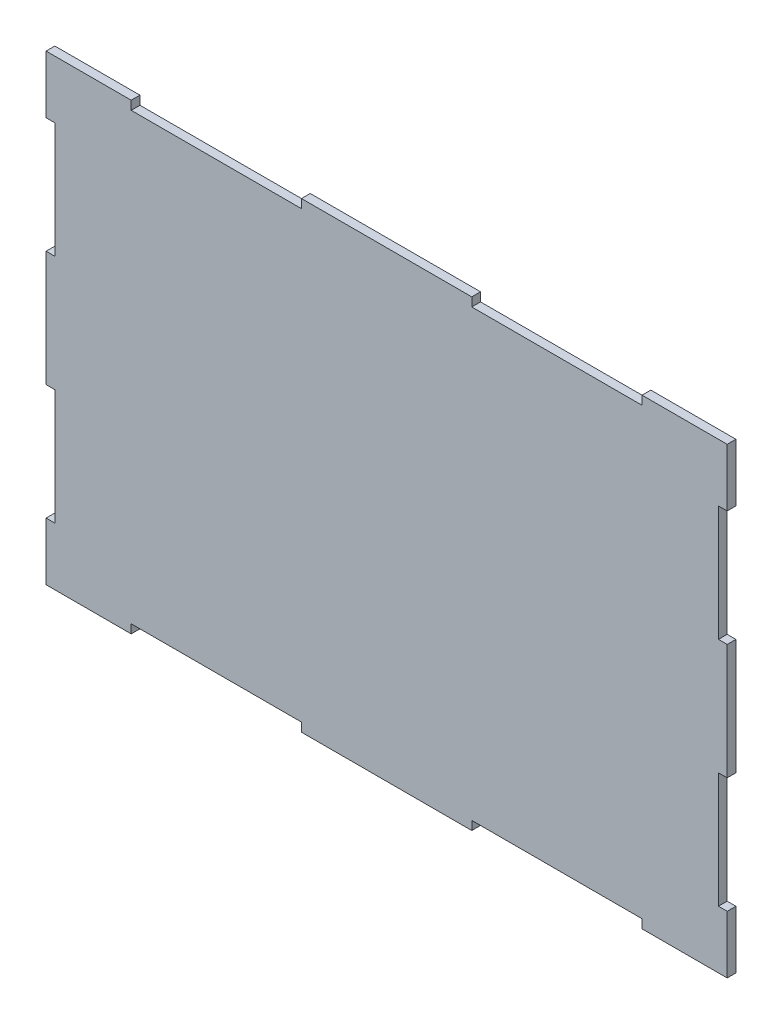
SolidWorks part; units mm, degrees
ref_plane "前视基准面" through (0, 0, 0) normal (0, 0, 1) x (1, 0, 0)
ref_plane "上视基准面" through (0, 0, 0) normal (0, 1, 0) x (1, 0, 0)
ref_plane "右视基准面" through (0, 0, 0) normal (1, 0, 0) x (0, 0, -1)
sketch "草图1" plane through (0, 0, 0) normal (0, 0, 1) x (1, 0, 0)
  line L5 (140, 95) -> (105, 95)
  line L6 (105, 91.4) -> (35, 91.4)
  line L7 (-35, 95) -> (-35, 91.4)
  line L8 (105, 95) -> (105, 91.4)
  line L9 (-105, 95) -> (-105, 91.4)
  line L10 (-105, 91.4) -> (-35, 91.4)
  line L11 (-140, 95) -> (-105, 95)
  line L12 (-35, 95) -> (35, 95)
  line L13 (35, 95) -> (35, 91.4)
  line L14 (-140, 23.75) -> (-136.4, 23.75)
  line L15 (-140, -95) -> (-140, -71.25)
  line L16 (-140, 71.25) -> (-136.4, 71.25)
  line L17 (-136.4, 71.25) -> (-136.4, 23.75)
  line L18 (-140, 95) -> (-140, 71.25)
  line L19 (-140, 23.75) -> (-140, -23.75)
  line L20 (-136.4, -71.25) -> (-136.4, -23.75)
  line L21 (-140, -71.25) -> (-136.4, -71.25)
  line L22 (-140, -23.75) -> (-136.4, -23.75)
  line L23 (35, -95) -> (35, -91.4)
  line L24 (-35, -95) -> (35, -95)
  line L25 (-140, -95) -> (-105, -95)
  line L26 (-105, -91.4) -> (-35, -91.4)
  line L27 (-105, -95) -> (-105, -91.4)
  line L28 (105, -95) -> (105, -91.4)
  line L29 (-35, -95) -> (-35, -91.4)
  line L30 (105, -91.4) -> (35, -91.4)
  line L31 (140, -95) -> (105, -95)
  line L32 (140, -23.75) -> (136.4, -23.75)
  line L33 (140, -71.25) -> (136.4, -71.25)
  line L34 (136.4, -71.25) -> (136.4, -23.75)
  line L35 (140, 23.75) -> (140, -23.75)
  line L36 (140, 95) -> (140, 71.25)
  line L37 (136.4, 71.25) -> (136.4, 23.75)
  line L38 (140, 71.25) -> (136.4, 71.25)
  line L39 (140, -95) -> (140, -71.25)
  line L40 (140, 23.75) -> (136.4, 23.75)
  point P0 (0, 0)
  point P14 (-70, 91.4)
  point P17 (70, 91.4)
  point P24 (-136.4, 47.5)
  point P27 (-136.4, -47.5)
  point P36 (70, -91.4)
  point P37 (-70, -91.4)
  point P46 (136.4, -47.5)
  point P47 (136.4, 47.5)
  dimension "D1" = 280
  dimension "D2" = 190
extrude "凸台-拉伸1" add sketch "草图1" along normal blind 3.6
